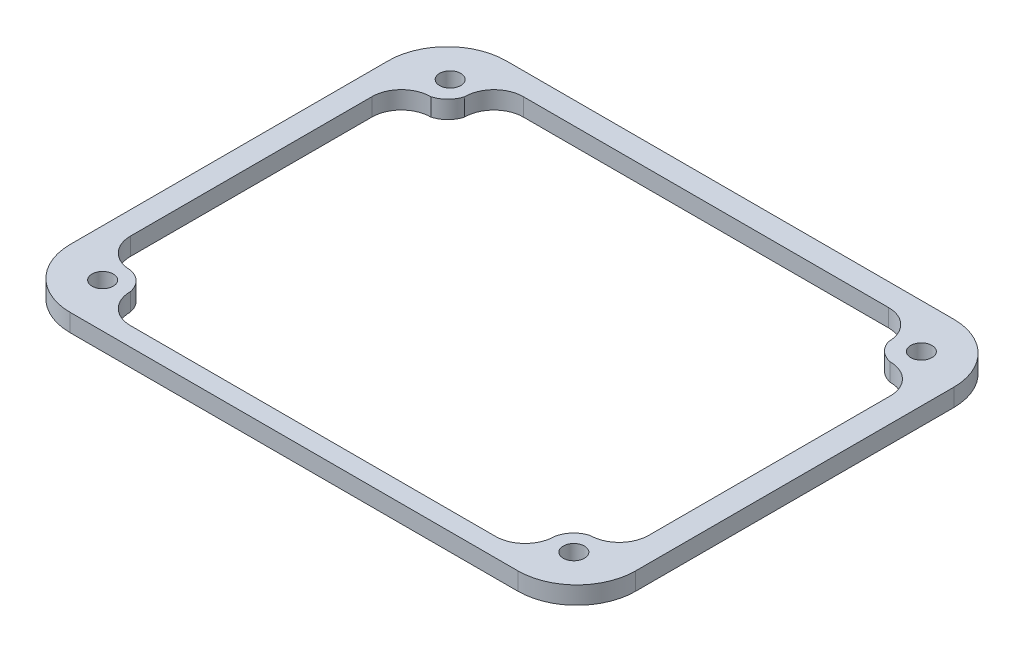
SolidWorks part; units mm, degrees
ref_plane "Ön Düzlem" through (0, 0, 0) normal (0, 0, 1) x (1, 0, 0)
ref_plane "Üst Düzlem" through (0, 0, 0) normal (0, 1, 0) x (1, 0, 0)
ref_plane "Sağ Düzlem" through (0, 0, 0) normal (1, 0, 0) x (0, 0, -1)
sketch "Çizim1" plane through (0, 0, 0) normal (0, 1, 0) x (1, 0, 0)
  line L1 (-37.8874, 37.1698) -> (38.1126, 37.1698)
  line L2 (-47.8874, 27.1698) -> (-47.8874, -26.8302)
  line L3 (-37.8874, -36.8302) -> (38.1126, -36.8302)
  line L4 (48.1126, 27.1698) -> (48.1126, -26.8302)
  line L6 (-44, 20.5) -> (-44, -20.5)
  line L7 (-43.8874, 33.6698) -> (44.1126, 33.6698) construction
  line L8 (-43.8874, 33.6698) -> (-43.8874, -33.3302) construction
  line L9 (-43.8874, -33.3302) -> (44.1126, -33.3302) construction
  line L10 (44.1126, 33.6698) -> (44.1126, -33.3302) construction
  line L12 (44, 20.5) -> (44, -20.5)
  line L13 (-44, 25.5) -> (-42.1176, 24.4091) construction
  line L14 (-44, -25.5) -> (-42.1176, -24.4091) construction
  line L15 (-31.1337, 33.3531) -> (30.8663, 33.3531)
  line L17 (-30.8376, -33.6624) -> (31.1624, -33.6624)
  line L19 (-36.1572, 33.3295) -> (-34.633, 31.9245) construction
  line L20 (-35.8307, -33.6698) -> (-34.3201, -32.2502) construction
  line L23 (42.1176, 24.4091) -> (44, 25.5) construction
  line L24 (42.1176, -24.4091) -> (44, -25.5) construction
  line L26 (34.8072, -32.0851) -> (36.158, -33.3302) construction
  line L27 (34.1684, 32.1076) -> (35.8419, 33.6803) construction
  circle A0 centre (-39.8874, 29.6698) radius 1.8
  circle A1 centre (40.1126, 29.6698) radius 1.8
  circle A2 centre (-39.8874, -29.3302) radius 1.8
  circle A3 centre (40.1126, -29.3302) radius 1.8
  arc A8 (44, 20.5) -> (39, 25.5) centre (39, 20.5) ccw
  arc A9 (44, -20.5) -> (39, -25.5) centre (39, -20.5) cw
  arc A10 (-39, -25.5) -> (-44, -20.5) centre (-39, -20.5) cw
  arc A11 (-44, 20.5) -> (-39, 25.5) centre (-39, 20.5) cw
  arc A12 (-35.8376, -28.6624) -> (-30.8376, -33.6624) centre (-30.8376, -28.6624) ccw
  arc A13 (31.1624, -33.6624) -> (36.1624, -28.6624) centre (31.1624, -28.6624) ccw
  arc A14 (35.8663, 28.3531) -> (30.8663, 33.3531) centre (30.8663, 28.3531) ccw
  arc A15 (-31.1337, 33.3531) -> (-36.1336, 28.3295) centre (-31.1337, 28.3531) ccw
  arc A16 (-39, 25.5) -> (-36.1336, 28.3295) centre (-40.0946, 29.4755) ccw
  arc A17 (35.8663, 28.3531) -> (39, 25.5) centre (39.7951, 29.5207) ccw
  arc A18 (39, -25.5) -> (36.1624, -28.6624) centre (40.187, -29.4194) ccw
  arc A19 (-39, -25.5) -> (-35.8376, -28.6624) centre (-39.764, -29.4264) cw
  arc A20 (-47.8874, 27.1698) -> (-37.8874, 37.1698) centre (-37.8874, 27.1698) cw
  arc A21 (48.1126, 27.1698) -> (38.1126, 37.1698) centre (38.1126, 27.1698) ccw
  arc A22 (38.1126, -36.8302) -> (48.1126, -26.8302) centre (38.1126, -26.8302) ccw
  arc A23 (-37.8874, -36.8302) -> (-47.8874, -26.8302) centre (-37.8874, -26.8302) cw
  point P0 (0, 0)
  point P6 (0, 0)
  point P21 (-47.8874, -36.8302)
  point P26 (48.1126, 37.1698)
  point P29 (-47.8874, 37.1698)
  point P30 (0, 0)
  point P47 (0, 0)
  dimension "D6" = 3.6
  dimension "D11" = 80
  dimension "D14" = 5
  dimension "D16" = 5
  dimension "D17" = 10
  dimension "D18" = 10
  dimension "D19" = 10
  dimension "D20" = 10
  dimension "D1" = 96
  dimension "D2" = 74
  dimension "D3" = 88
  dimension "D4" = 67
  dimension "D5" = 3.5
  dimension "D7" = 4
  dimension "D8" = 4
  dimension "D12" = 88
  dimension "D13" = 51
  dimension "D15" = 72
  dimension "D21" = 59
  dimension "D9" = 2
  dimension "D10" = 2
extrude "Yükseklik-Ekstrüzyon1" add sketch "Çizim1" along normal blind 3
